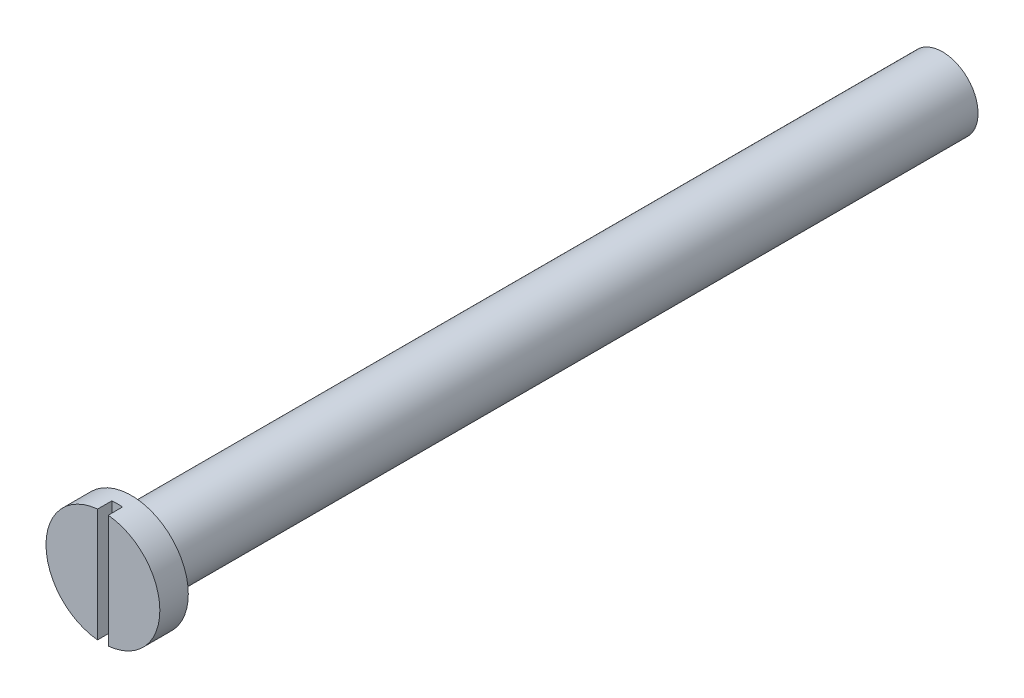
SolidWorks part; units mm, degrees
ref_plane "前视基准面" through (0, 0, 0) normal (0, 0, 1) x (1, 0, 0)
ref_plane "上视基准面" through (0, 0, 0) normal (0, 1, 0) x (1, 0, 0)
ref_plane "右视基准面" through (0, 0, 0) normal (1, 0, 0) x (0, 0, -1)
sketch "草图1" plane through (0, 0, 0) normal (0, 0, 1) x (1, 0, 0)
  circle A0 centre (0, 0) radius 5
  dimension "D1" = 10
extrude "凸台-拉伸1" add sketch "草图1" along normal blind 114
cosmetic thread "装饰螺纹线2" parameters "D1"=10, "D2"=4.134
sketch "草图2" plane through (0, 0, 114) normal (0, 0, 1) x (1, 0, 0)
  circle A0 centre (0, 0) radius 8
  dimension "D1" = 16
extrude "凸台-拉伸2" add sketch "草图2" along normal blind 4
sketch "草图4" plane through (0, 0, 118) normal (0, 0, 1) x (1, 0, 0)
  line L1 (-0.75, 9.78) -> (0.75, 9.78)
  line L2 (-0.75, 9.78) -> (-0.75, -9.78)
  line L3 (-0.75, -9.78) -> (0.75, -9.78)
  line L4 (0.75, 9.78) -> (0.75, -9.78)
  line L5 (-0.75, 9.78) -> (0.75, -9.78) construction
  line L6 (-0.75, -9.78) -> (0.75, 9.78) construction
  point P0 (0, 0)
  dimension "D1" = 1.5
extrude "切除-拉伸1" cut sketch "草图4" against normal blind 2
sketch "草图5" plane through (0, 0, 0) normal (0, 0, -1) x (-1, 0, 0)
  point P0 (0, 0)
  point P1 (-8.9921, 4.042)
hole_wizard "M8 螺纹孔的螺纹孔钻头1" positions "草图6" profile "草图8" hole size "M8" standard "GB"
sketch "草图6" plane through (0, 0, 0) normal (0, 0, -1) x (-1, 0, 0)
  point P0 (0, 0)
sketch "草图8" plane through (0, 0, 0) normal (1, 0, 0) x (0, 1, 0)
  line L0 (0, 0) -> (0, 17.0429)
  line L1 (0, 17.0429) -> (3.4, 15)
  line L2 (3.4, 15) -> (3.4, 0)
  line L5 (3.4, 0) -> (0, 0)
  line L10 (0, 17.0429) -> (-3.4, 15) construction
  line L11 (0, -6.35) -> (0, 107.95) construction
  dimension "孔直径" = 6.8
  dimension "孔深度" = 15
  dimension "导头角度" = 118
